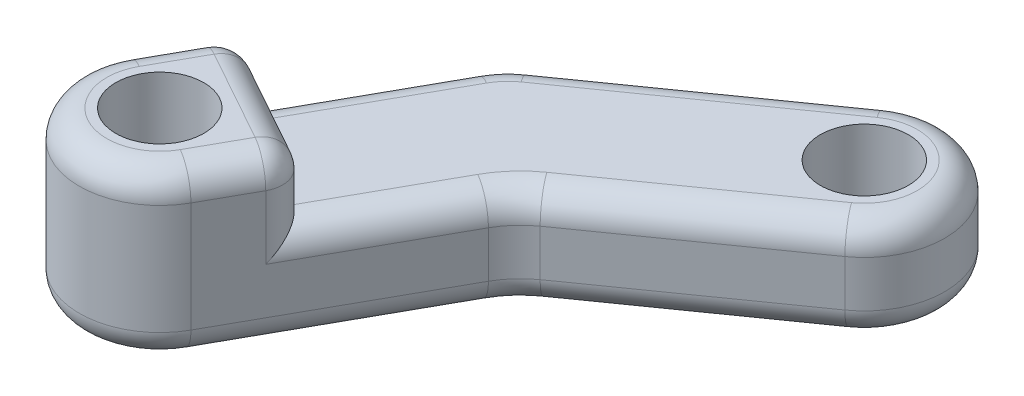
SolidWorks part; units mm, degrees
ref_plane "Front Plane" through (0, 0, 0) normal (0, 0, 1) x (1, 0, 0)
ref_plane "Top Plane" through (0, 0, 0) normal (0, 1, 0) x (1, 0, 0)
ref_plane "Right Plane" through (0, 0, 0) normal (1, 0, 0) x (0, 0, -1)
sketch "Sketch1" plane through (0, 0, 0) normal (0, 1, 0) x (1, 0, 0)
  line L26 (-14.6766, 12.0588) -> (-10.1606, 3.9514)
  line L27 (-9.2692, 2.96) -> (-1.6862, -2.39)
  line L28 (-9.566, 14.9056) -> (-5.6988, 7.9629)
  line L29 (-4.8074, 6.9715) -> (1.6862, 2.39)
  line L30 (-9.7707, 3.4056) -> (-5.3089, 7.417) construction
  line L31 (-12.1213, 13.4822) -> (0, 0) construction
  circle A14 centre (-12.1213, 13.4822) radius 1.6
  circle A15 centre (0, 0) radius 1.6
  arc A17 (-1.6862, -2.39) -> (1.6862, 2.39) centre (0, 0) ccw
  arc A18 (-14.6766, 12.0588) -> (-9.566, 14.9056) centre (-12.1213, 13.4822) cw
  arc A19 (-5.6988, 7.9629) -> (-4.8074, 6.9715) centre (-3.0779, 9.4228) ccw
  arc A20 (-10.1606, 3.9514) -> (-9.2692, 2.96) centre (-7.5398, 5.4113) ccw
  point P3 (-7.5398, 5.4113)
  point P17 (-6.0607, 6.7411)
  dimension "D4" = 5.85
  dimension "D1" = 3
  dimension "D2" = 18.13
  dimension "D3" = 5.85
extrude "Boss-Extrude1" add sketch "Sketch1" along normal blind 6
fillet "Fillet2" radius 1 16 edges at (-5.3089, 0, -7.417) (-5.3089, 6, -7.417) (-1.5606, 0, -4.6807) (2.39, 0, 1.6862) (-5.4777, 0, -0.285) (-9.7707, 0, -3.4056) (-12.4186, 0, -8.0051) (-13.5447, 0, -16.0375) (-7.6324, 0, -11.4342) (-1.5606, 6, -4.6807) (2.39, 6, 1.6862) (-5.4777, 6, -0.285) (-9.7707, 6, -3.4056) (-12.4186, 6, -8.0051) (-13.5447, 6, -16.0375) (-7.6324, 6, -11.4342)
sketch "Sketch3" plane through (0, 6, 0) normal (0, 1, 0) x (1, 0, 0)
  line L0 (-9.566, 14.9056) -> (-5.6988, 7.9629) construction
  line L1 (-4.8074, 6.9715) -> (1.6862, 2.39) construction
  line L2 (-1.6862, -2.39) -> (-9.2692, 2.96) construction
  line L3 (-10.1606, 3.9514) -> (-14.6766, 12.0588) construction
  line L4 (-6.5724, 7.4763) -> (-10.4396, 14.419)
  line L5 (-13.803, 12.5455) -> (-9.287, 4.4381)
  line L6 (-8.6928, 3.7771) -> (-1.1097, -1.5729)
  line L7 (1.1097, 1.5729) -> (-5.3839, 6.1544)
  line L8 (-6.5724, 7.4763) -> (-8.9798, 11.7981)
  line L9 (-12.3432, 9.9246) -> (-9.287, 4.4381)
  line L10 (-8.6928, 3.7771) -> (-1.1097, -1.5729)
  line L11 (1.1097, 1.5729) -> (-5.3839, 6.1544)
  line L12 (-8.1061, 12.2848) -> (-5.6988, 7.9629)
  line L13 (-4.8074, 6.9715) -> (1.6862, 2.39)
  line L14 (-1.6862, -2.39) -> (-9.2692, 2.96)
  line L15 (-10.1606, 3.9514) -> (-13.2168, 9.438)
  line L16 (-13.2168, 9.438) -> (-8.1061, 12.2848)
  circle A0 centre (-12.1213, 13.4822) radius 1.6 construction
  circle A2 centre (0, 0) radius 1.6 construction
  circle A3 centre (0, 0) radius 1.6
  arc A4 (-10.4396, 14.419) -> (-13.803, 12.5455) centre (-12.1213, 13.4822) ccw
  arc A5 (-9.287, 4.4381) -> (-8.6928, 3.7771) centre (-7.5398, 5.4113) ccw
  arc A6 (-1.1097, -1.5729) -> (1.1097, 1.5729) centre (0, 0) ccw
  arc A7 (-6.5724, 7.4763) -> (-5.3839, 6.1544) centre (-3.0779, 9.4228) ccw
  arc A9 (-9.287, 4.4381) -> (-8.6928, 3.7771) centre (-7.5398, 5.4113) ccw
  arc A10 (-1.1097, -1.5729) -> (1.1097, 1.5729) centre (0, 0) ccw
  arc A11 (-6.5724, 7.4763) -> (-5.3839, 6.1544) centre (-3.0779, 9.4228) ccw
  arc A12 (-5.6988, 7.9629) -> (-4.8074, 6.9715) centre (-3.0779, 9.4228) ccw construction
  arc A13 (-1.6862, -2.39) -> (1.6862, 2.39) centre (0, 0) ccw construction
  arc A14 (-10.1606, 3.9514) -> (-9.2692, 2.96) centre (-7.5398, 5.4113) ccw construction
  arc A15 (-5.6988, 7.9629) -> (-4.8074, 6.9715) centre (-3.0779, 9.4228) ccw
  arc A16 (-1.6862, -2.39) -> (1.6862, 2.39) centre (0, 0) ccw
  arc A17 (-10.1606, 3.9514) -> (-9.2692, 2.96) centre (-7.5398, 5.4113) ccw
  line M11 (-6.5724, 7.4763) -> (-10.4396, 14.419)
  line M13 (-13.803, 12.5455) -> (-9.287, 4.4381)
  arc M14 (-9.287, 4.4381) -> (-8.6928, 3.7771) centre (-7.5398, 5.4113) ccw
  line M15 (-8.6928, 3.7771) -> (-1.1097, -1.5729)
  arc M16 (-1.1097, -1.5729) -> (1.1097, 1.5729) centre (0, 0) ccw
  line M17 (1.1097, 1.5729) -> (-5.3839, 6.1544)
  arc M18 (-5.3839, 6.1544) -> (-6.5724, 7.4763) centre (-3.0779, 9.4228) cw
  circle M20 centre (0, 0) radius 1.6
  dimension "D2" = 3
  dimension "D1" = 0
extrude "Cut-Extrude1" cut sketch "Sketch3" against normal blind 2.3175 contours L16 M13 M14 M15 M16 M17 M18 M11 M20 | L15 A17 L14 A16 L13 A15 L12 L16 M11 M18 M17 M16 M15 M14 M13
fillet "Fillet3" radius 1 7 edges at (-11.6887, 3.6825, -6.6947) (-9.7707, 3.6825, -3.4056) (-5.4777, 3.6825, -0.285) (-6.9025, 3.6825, -10.1238) (-5.3089, 3.6825, -7.417) (-1.5606, 3.6825, -4.6807) (2.39, 3.6825, 1.6862)
fillet "Fillet4" radius 1 5 edges at (-12.9609, 5.7071, -9.5805) (-10.6615, 6, -10.8614) (-8.362, 5.7071, -12.1422) (-13.2168, 3.8413, -9.438) (-8.1061, 3.8413, -12.2848)
ref_plane "Plane1" through (0, 0, 16.5633) normal (0, 0, 1) x (1, 0, 0)
mirror "Mirror12" about plane through (0, 0, 16.5633) normal (0, 0, 1) of bodies 102
delete or keep bodies "Body-Delete/Keep 1" type delete bodies bodies 102
